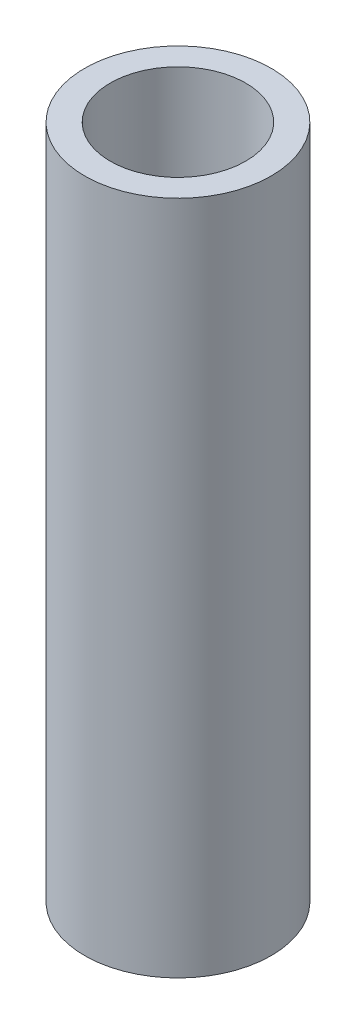
SolidWorks part; units mm, degrees
ref_plane "Ebene vorne" through (0, 0, 0) normal (0, 0, 1) x (1, 0, 0)
ref_plane "Ebene oben" through (0, 0, 0) normal (0, 1, 0) x (1, 0, 0)
ref_plane "Ebene rechts" through (0, 0, 0) normal (1, 0, 0) x (0, 0, -1)
sketch "Skizze1" plane through (0, 0, 0) normal (0, 0, 1) x (1, 0, 0)
  line L0 (-3.4, 0) -> (-3.4, 15)
  line L1 (-3.4, 15) -> (0, 15)
  line L2 (0, 15) -> (0, 15.4)
  line L3 (0, 15.4) -> (-3.05, 15.4)
  line L4 (-3.05, 15.4) -> (-3.05, 30.4)
  line L5 (-3.05, 30.4) -> (-4.2, 30.4)
  line L6 (-4.2, 30.4) -> (-4.2, 0)
  line L7 (-4.2, 0) -> (-3.4, 0)
  line L8 (0, 0) -> (0, 30.4) construction
  point P12 (0, 15.2)
  dimension "D1" = 6.1
  dimension "D2" = 6.8
  dimension "D3" = 0.4
  dimension "D4" = 15
  dimension "D5" = 0.8
revolve "Rotation1" add sketch "Skizze1" angle 360 about L8
